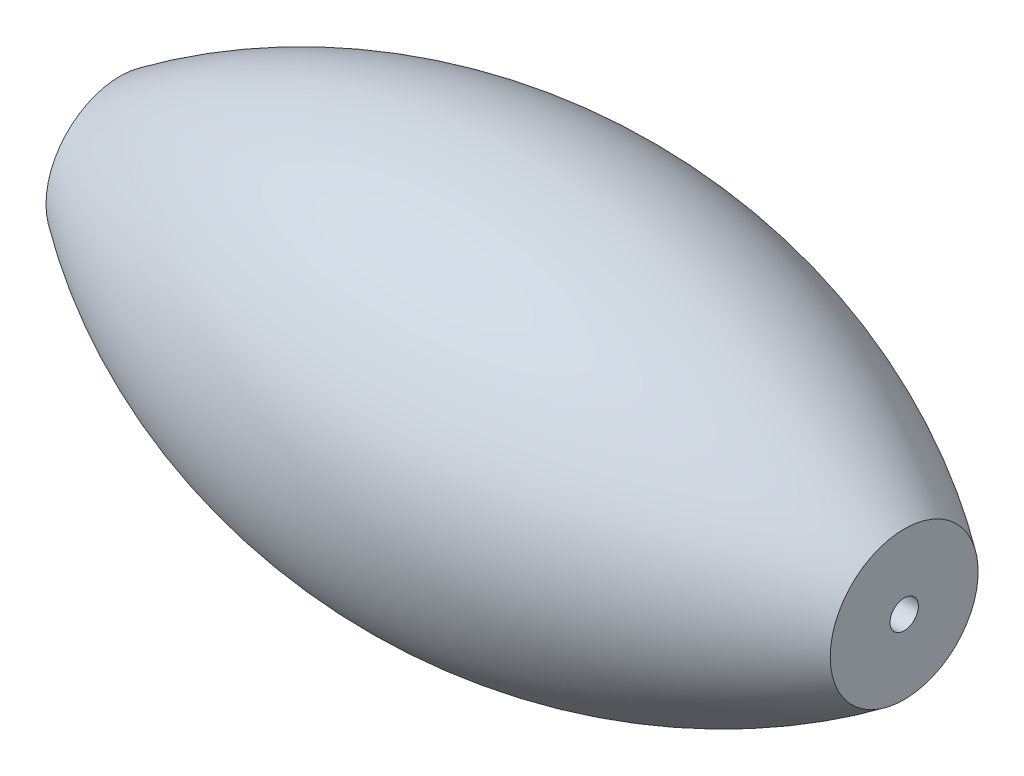
SolidWorks part; units mm, degrees
ref_plane "Alzado" through (0, 0, 0) normal (0, 0, 1) x (1, 0, 0)
ref_plane "Planta" through (0, 0, 0) normal (0, 1, 0) x (1, 0, 0)
ref_plane "Vista lateral" through (0, 0, 0) normal (1, 0, 0) x (0, 0, -1)
sketch "Croquis2" plane through (0, 0, 0) normal (0, 0, 1) x (1, 0, 0)
  line L0 (0, 106.514) -> (0, -106.514) construction
  line L1 (106.514, 0) -> (-106.514, 0) construction
  line L2 (62.1334, 86.514) -> (62.1334, 0) construction
  line L3 (-62.1334, 86.514) -> (-62.1334, -86.514) construction
  line L4 (-62.1334, 86.514) -> (62.1334, 86.514) construction
  line L5 (-62.1334, 74.7945) -> (62.1334, 74.7945) construction
  line L6 (-62.1334, 86.514) -> (-62.1334, 74.7945)
  line L7 (-62.1334, 74.7945) -> (62.1334, 74.7945)
  line L8 (62.1334, 74.7945) -> (62.1334, 86.514)
  arc A0 (62.1334, 86.514) -> (-62.1334, 86.514) centre (0, 0) ccw
  point P8 (-252.304, 31.6535)
  dimension "D1" = 11.7195
  dimension "D2" = 124.2668
revolve "Revolución1" add sketch "Croquis2" angle 360 about L7
sketch "Croquis5" plane through (62.1334, 0, 0) normal (1, 0, 0) x (0, 0, -1)
  line L0 (0, 86.514) -> (0, 63.075) construction
  line L1 (-11.7195, 74.7945) -> (11.7195, 74.7945) construction
  circle A1 centre (0, 74.7945) radius 11.7195 construction
hole_wizard "Taladro de margen para #81" positions "Croquis9" profile "Croquis8" hole size "#8" standard "Ansi Inch"
sketch "Croquis9" plane through (62.1334, 0, 0) normal (1, 0, 0) x (0, 0, -1)
  line L0 (0, 86.514) -> (0, 63.075) construction
  point P0 (0, 74.7945)
sketch "Croquis8" plane through (62.1334, 74.7945, 0) normal (0, 1, 0) x (0, 0, -1)
  line L0 (0, 0) -> (0, 125.6165)
  line L1 (0, 125.6165) -> (2.2479, 124.2658)
  line L2 (2.2479, 124.2658) -> (2.2479, 0)
  line L5 (2.2479, 0) -> (0, 0)
  line L10 (0, 125.6165) -> (-2.2479, 124.2658) construction
  line L11 (0, -6.35) -> (0, 107.95) construction
  dimension "Diámetro de taladro" = 4.4958
  dimension "Profundidad de taladro" = 124.2658
  dimension "Ángulo de perforador" = 118
